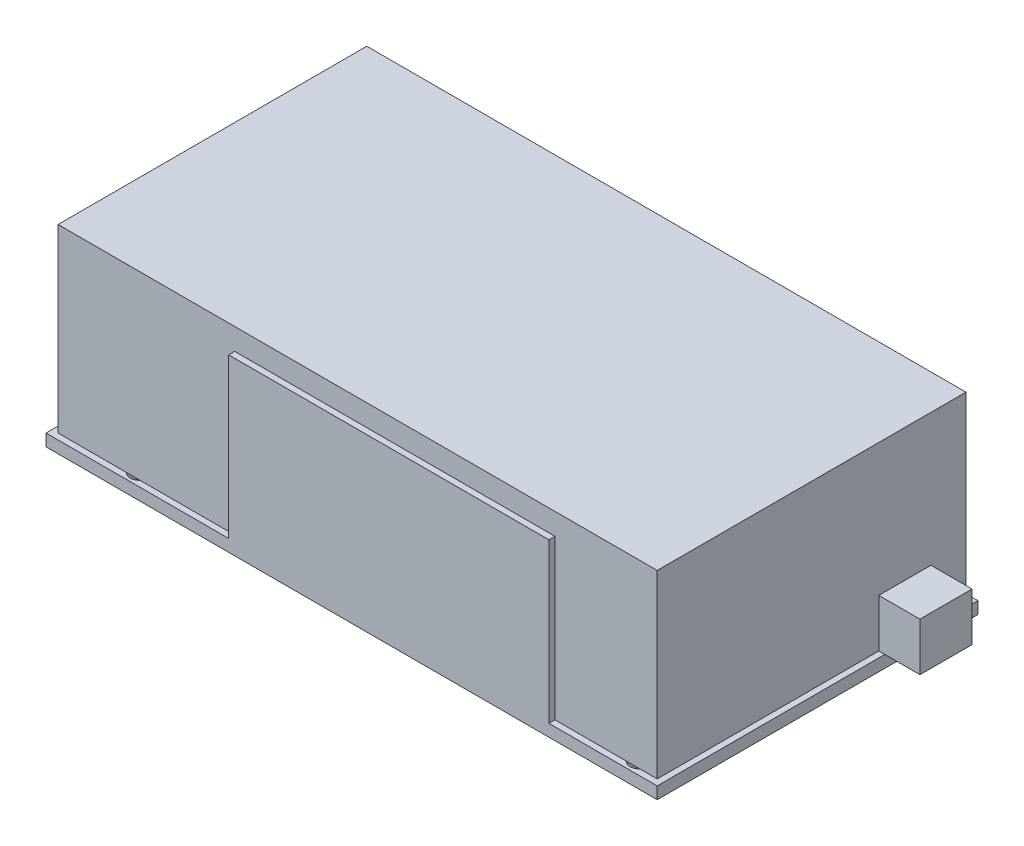
SolidWorks part; units mm, degrees
ref_plane "Plano frontal" through (0, 0, 0) normal (0, 0, 1) x (1, 0, 0)
ref_plane "Plano superior" through (0, 0, 0) normal (0, 1, 0) x (1, 0, 0)
ref_plane "Plano direito" through (0, 0, 0) normal (1, 0, 0) x (0, 0, -1)
sketch "Esboço1" plane through (0, 0, 0) normal (0, 1, 0) x (1, 0, 0)
  line L1 (-50.775, -26.65) -> (50.775, -26.65)
  line L2 (-50.775, -26.65) -> (-50.775, 26.65)
  line L3 (-50.775, 26.65) -> (50.775, 26.65)
  line L4 (50.775, -26.65) -> (50.775, 26.65)
  line L5 (-50.775, -26.65) -> (50.775, 26.65) construction
  line L6 (-50.775, 26.65) -> (50.775, -26.65) construction
  point P0 (0, 0)
  dimension "D1" = 53.3
  dimension "D2" = 101.55
extrude "Ressalto-extrusão1" add sketch "Esboço1" along normal blind 2
sketch "Esboço2" plane through (0, 2, 0) normal (0, 1, 0) x (1, 0, 0)
  line L2 (50.775, 26.65) -> (-50.775, 26.65) construction
  line L3 (-20.425, 26.65) -> (32.775, 26.65)
  line L4 (32.775, 26.65) -> (32.775, -26.65)
  line L5 (-50.775, -26.65) -> (50.775, -26.65) construction
  line L6 (32.775, -26.65) -> (-20.425, -26.65)
  line L7 (-20.425, -26.65) -> (-20.425, 26.65)
  line L10 (50.775, -26.65) -> (50.775, 26.65) construction
  point P0 (0, 0)
  dimension "D1" = 53.2
  dimension "D2" = 18
extrude "Ressalto-extrusão2" add sketch "Esboço2" along normal blind 26.4167
sketch "Esboço4" plane through (0, 28.4167, 0) normal (0, 1, 0) x (1, 0, 0)
sketch "Esboço5" plane through (0, 2, 0) normal (0, 1, 0) x (1, 0, 0)
  line L0 (-50.775, 26.65) -> (-50.775, -26.65) construction
  line L1 (-20.425, 26.65) -> (-50.775, 26.65) construction
  line L2 (-50.775, -26.65) -> (-20.425, -26.65) construction
  line L3 (50.775, 26.65) -> (32.775, 26.65) construction
  line L4 (32.775, -26.65) -> (50.775, -26.65) construction
  line L5 (50.775, -26.65) -> (50.775, 26.65) construction
  circle A0 centre (-37.275, -24.65) radius 1.5
  circle A1 centre (45.775, -24.65) radius 1.5
  circle A2 centre (-36.275, 24.65) radius 1.5
  circle A3 centre (39.275, 24.65) radius 1.5
  point P10 (-35.6, 26.65)
  dimension "D1" = 3
  dimension "D2" = 3
  dimension "D3" = 3
  dimension "D4" = 3
  dimension "D5" = 14.5
  dimension "D6" = 2
  dimension "D7" = 2
  dimension "D8" = 2
  dimension "D9" = 2
  dimension "D10" = 13.5
  dimension "D11" = 11.5
  dimension "D12" = 5
extrude "Corte-extrusão2" cut sketch "Esboço5" against normal blind 64.64 and the other way through all
sketch "Esboço6" plane through (0, 2, 0) normal (0, 1, 0) x (1, 0, 0)
  line L0 (50.775, -26.65) -> (50.775, 26.65) construction
  line L1 (-49.775, 25.65) -> (49.775, 25.65)
  line L2 (-49.775, 25.65) -> (-49.775, -25.65)
  line L3 (-49.775, -25.65) -> (49.775, -25.65)
  line L4 (49.775, 25.65) -> (49.775, -25.65)
  line L5 (50.775, 26.65) -> (32.775, 26.65) construction
  line L6 (-50.775, 26.65) -> (-50.775, -26.65) construction
  line L7 (-50.775, -26.65) -> (-20.425, -26.65) construction
  dimension "D1" = 1
  dimension "D2" = 1
  dimension "D3" = 1
  dimension "D4" = 1
extrude "Ressalto-extrusão4" add sketch "Esboço6" along normal blind 30
sketch "Esboço7" plane through (0, 2, 0) normal (0, 1, 0) x (1, 0, 0)
  line L1 (39.6809, 11.1675) -> (56.6065, 11.1675)
  line L2 (39.6809, 11.1675) -> (39.6809, 19.8313)
  line L3 (39.6809, 19.8313) -> (56.6065, 19.8313)
  line L4 (56.6065, 11.1675) -> (56.6065, 19.8313)
extrude "Ressalto-extrusão5" add sketch "Esboço7" along normal blind 8
